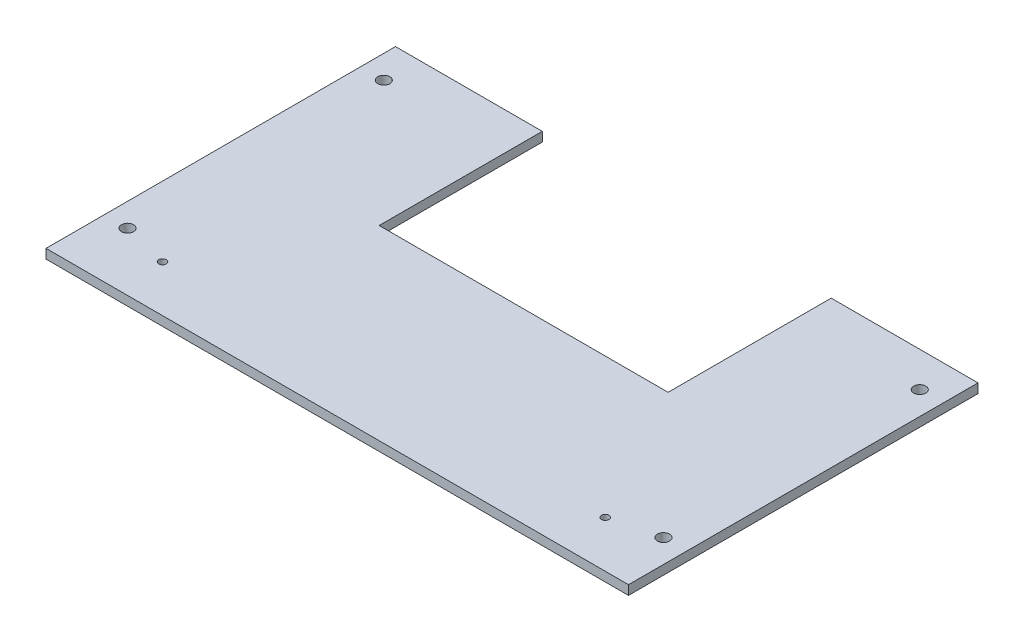
SolidWorks part; units mm, degrees
ref_plane "Alzado" through (0, 0, 0) normal (0, 0, 1) x (1, 0, 0)
ref_plane "Planta" through (0, 0, 0) normal (0, 1, 0) x (1, 0, 0)
ref_plane "Vista lateral" through (0, 0, 0) normal (1, 0, 0) x (0, 0, -1)
sketch "Croquis1" plane through (0, 0, 0) normal (0, 1, 0) x (1, 0, 0)
  line L1 (-125, -75) -> (125, -75)
  line L2 (-125, -75) -> (-125, 75)
  line L3 (-125, 75) -> (125, 75)
  line L4 (125, -75) -> (125, 75)
  line L5 (-125, -75) -> (125, 75) construction
  line L6 (-125, 75) -> (125, -75) construction
  point P0 (0, 0)
  dimension "D1" = 250
  dimension "D2" = 150
extrude "Saliente-Extruir1" add sketch "Croquis1" along normal blind 4
sketch "Croquis2" plane through (0, 4, 0) normal (0, 1, 0) x (1, 0, 0)
  line L0 (125, 75) -> (-125, 75) construction
  line L1 (-62, 5) -> (62, 5)
  line L2 (-62, 5) -> (-62, 75)
  line L3 (-62, 75) -> (62, 75)
  line L4 (62, 5) -> (62, 75)
  line L5 (-125, 75) -> (-125, -75) construction
  circle A0 centre (-115, 60) radius 2.6
  circle A1 centre (115, 60) radius 2.6
  circle A2 centre (115, -50) radius 2.6
  circle A3 centre (-115, -50) radius 2.6
  dimension "D4" = 5.2
  dimension "D1" = 62
  dimension "D2" = 62
  dimension "D3" = 70
  dimension "D5" = 15
  dimension "D6" = 10
  dimension "D7" = 2
  dimension "D8" = 2
extrude "Cortar-Extruir1" cut sketch "Croquis2" against normal blind 4
sketch "Croquis3" plane through (0, 4, 0) normal (0, 1, 0) x (1, 0, 0)
  line L7 (-125, -75) -> (125, -75) construction
  line L8 (125, -75) -> (125, 75) construction
  circle A0 centre (95, -55) radius 1.6
  circle A1 centre (-95, -55) radius 1.6
  dimension "D4" = 3.2
  dimension "D1" = 20
  dimension "D2" = 30
  dimension "D8" = 190
  dimension "D7" = 2
extrude "Cortar-Extruir2" cut sketch "Croquis3" against normal blind 10
